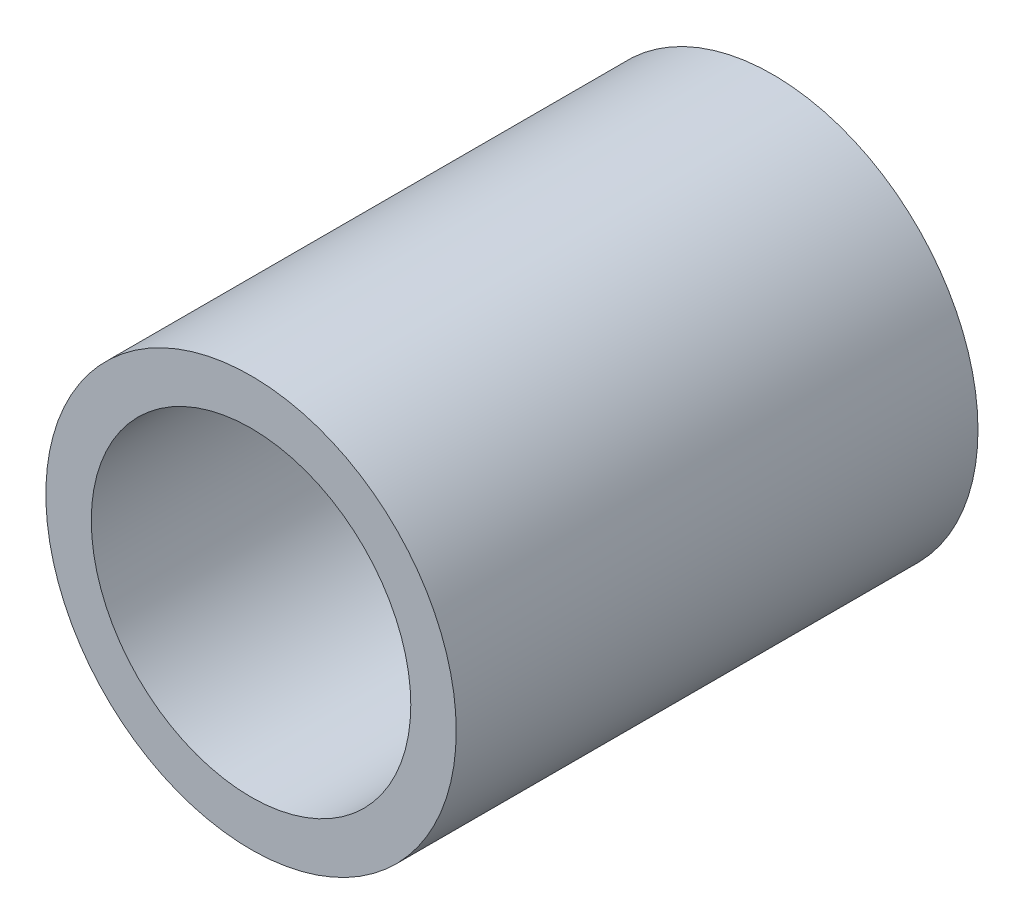
SolidWorks part; units mm, degrees
material "ABS"
ref_plane "Front Plane" through (0, 0, 0) normal (0, 0, 1) x (1, 0, 0)
ref_plane "Top Plane" through (0, 0, 0) normal (0, 1, 0) x (1, 0, 0)
ref_plane "Right Plane" through (0, 0, 0) normal (1, 0, 0) x (0, 0, -1)
sketch "Sketch1" plane through (0, 0, 0) normal (0, 0, 1) x (1, 0, 0)
  circle A0 centre (0, 0) radius 3.5
  circle A1 centre (0, 0) radius 2.725
  dimension "D1" = 7
  dimension "D2" = 5.45
extrude "Boss-Extrude1" add sketch "Sketch1" along normal blind 8.9
equation "\"D2@Sketch1\"=5+\"print_free@Parameters@Parameters.SLDPRT\""
